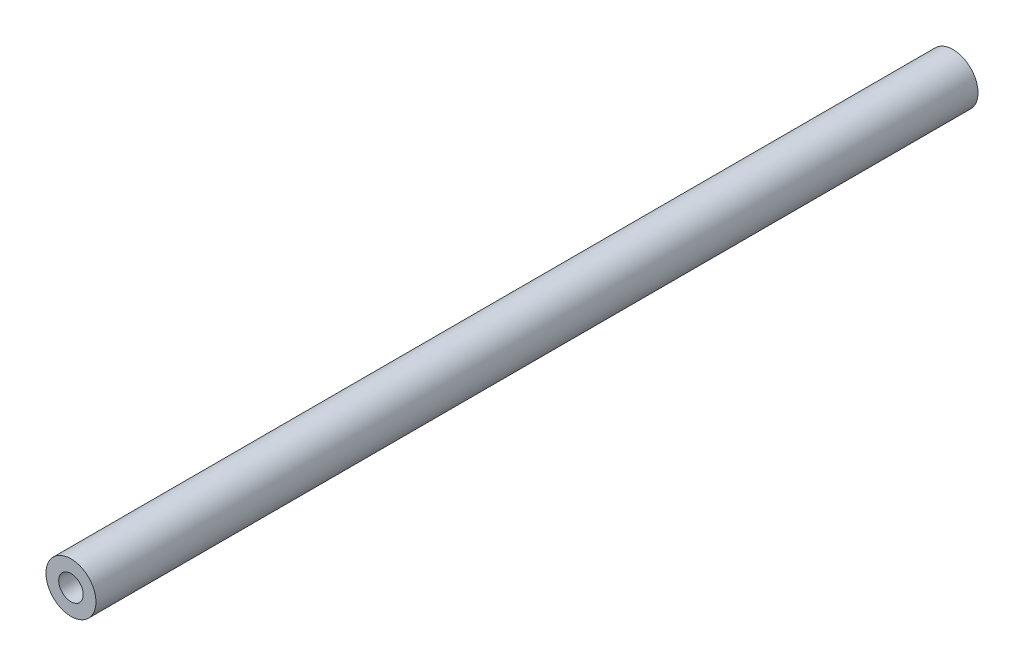
SolidWorks part; units mm, degrees
ref_plane "Front Plane" through (0, 0, 0) normal (0, 0, 1) x (1, 0, 0)
ref_plane "Top Plane" through (0, 0, 0) normal (0, 1, 0) x (1, 0, 0)
ref_plane "Right Plane" through (0, 0, 0) normal (1, 0, 0) x (0, 0, -1)
sketch "Sketch1" plane through (0, 0, 0) normal (0, 0, 1) x (1, 0, 0)
  circle A0 centre (0, 0) radius 6.477
  circle A1 centre (0, 0) radius 3.175
  dimension "D1" = 12.954
  dimension "D2" = 6.35
extrude "Boss-Extrude1" add sketch "Sketch1" along normal blind 228.6
sketch "Sketch2" plane through (0, 0, 0) normal (0, 1, 0) x (1, 0, 0)
  line L1 (-6.477, -192.0875) -> (1.143, -192.0875)
  line L2 (-6.477, -192.0875) -> (-6.477, -184.15)
  line L3 (-6.477, -184.15) -> (1.143, -184.15)
  line L4 (1.143, -192.0875) -> (1.143, -184.15)
  line L5 (-6.477, 0) -> (-6.477, -228.6) construction
  dimension "D1" = 184.15
  dimension "D2" = 7.62
  dimension "D3" = 7.9375
  dimension "D4" = 0
extrude "Cut-Extrude1" cut sketch "Sketch2" against normal through all
